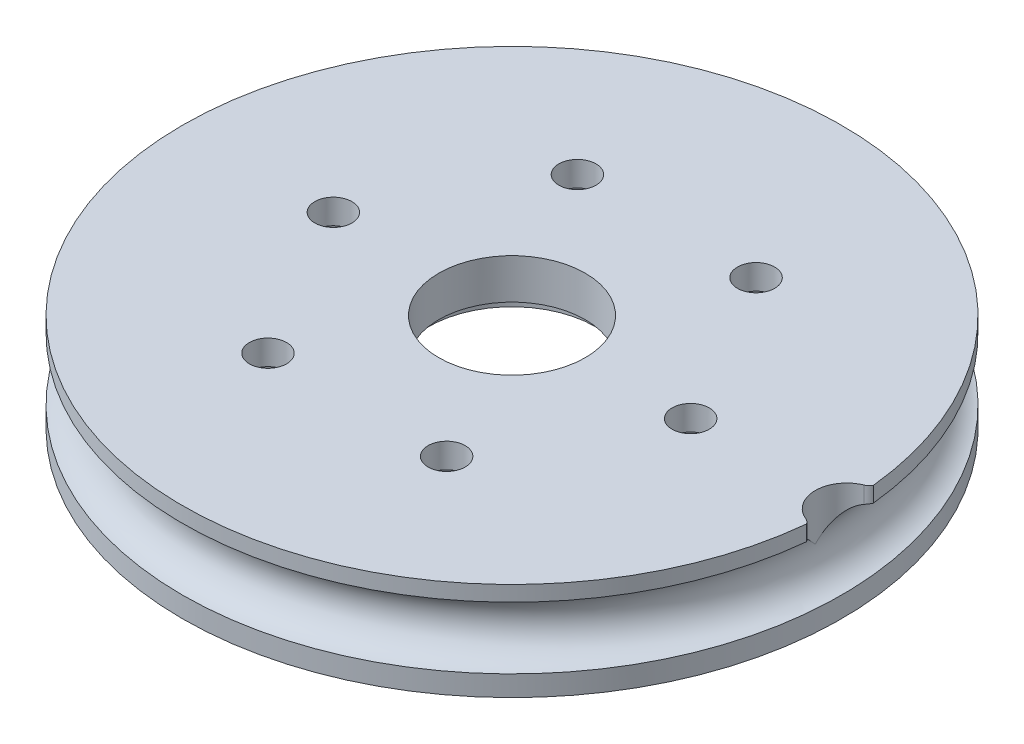
SolidWorks part; units mm, degrees
ref_plane "Front Plane" through (0, 0, 0) normal (0, 0, 1) x (1, 0, 0)
ref_plane "Top Plane" through (0, 0, 0) normal (0, 1, 0) x (1, 0, 0)
ref_plane "Right Plane" through (0, 0, 0) normal (1, 0, 0) x (0, 0, -1)
sketch "Sketch1" plane through (0, 0, 0) normal (0, 1, 0) x (1, 0, 0)
  line L0 (3.8128, 15.469) -> (8.2942, 33.6508) construction
  circle A0 centre (0, 0) radius 25.1 construction
  circle A1 centre (0, 25.1) radius 2
  circle A2 centre (11.6646, 22.2249) radius 2
  circle A3 centre (20.6569, 14.2584) radius 2
  circle A4 centre (24.917, 3.0255) radius 2
  circle A5 centre (23.4689, -8.9006) radius 2
  circle A6 centre (16.6444, -18.7876) radius 2
  circle A7 centre (6.0068, -24.3706) radius 2
  circle A8 centre (-6.0068, -24.3706) radius 2
  circle A9 centre (-16.6444, -18.7876) radius 2
  circle A10 centre (-23.4689, -8.9006) radius 2
  circle A11 centre (-24.917, 3.0255) radius 2
  circle A12 centre (-20.6569, 14.2584) radius 2
  arc A16 (1.6408, 23.5429) -> (9.4881, 21.6087) centre (5.6478, 22.9142) cw
  arc A17 (12.3938, 20.0837) -> (18.4433, 14.7242) centre (15.6497, 17.6649) cw
  arc A18 (20.3075, 12.0235) -> (23.1735, 4.4666) centre (22.0664, 8.3687) cw
  arc A19 (23.569, 1.2089) -> (22.5948, -6.8142) centre (23.4279, -2.8447) cw
  arc A20 (21.4311, -9.8826) -> (16.84, -16.534) centre (19.4224, -13.4063) cw
  arc A21 (14.3837, -18.7102) -> (7.2273, -22.4661) centre (10.9675, -20.8968) cw
  arc A22 (4.0411, -23.2514) -> (-4.0411, -23.2514) centre (0, -23.6) cw
  arc A23 (-7.2273, -22.4661) -> (-14.3837, -18.7102) centre (-10.9675, -20.8968) cw
  arc A24 (-16.84, -16.534) -> (-21.4311, -9.8826) centre (-19.4224, -13.4063) cw
  arc A25 (-22.5948, -6.8142) -> (-23.569, 1.2089) centre (-23.4279, -2.8447) cw
  arc A26 (-23.1735, 4.4666) -> (-20.3075, 12.0235) centre (-22.0664, 8.3687) cw
  arc A27 (-18.4433, 14.7242) -> (-12.3938, 20.0837) centre (-15.6497, 17.6649) cw
  circle A30 centre (0, 0) radius 4 construction
  circle A31 centre (0, 0) radius 23.6 construction
  circle A32 centre (0, 0) radius 32.15
  circle A33 centre (0, 0) radius 1.5
  circle A34 centre (-11.6646, 22.2249) radius 2
  arc A37 (-9.4881, 21.6087) -> (-1.6408, 23.5429) centre (-5.6478, 22.9142) cw
  dimension "D1" = 50.2
  dimension "D2" = 4
  dimension "D8" = 8
  dimension "D4" = 64.3
  dimension "D6" = 3
  dimension "D5" = 0
  dimension "D9" = 1.5
  dimension "D3" = 13
  dimension "D7" = 13
extrude "Boss-Extrude1" add sketch "Sketch1" along normal blind 4.5
sketch "Sketch2" plane through (0, 4.5, 0) normal (0, 1, 0) x (1, 0, 0)
  circle A0 centre (0, 0) radius 4 construction
  circle A2 centre (0, 0) radius 4
  circle A3 centre (0, 0) radius 32.15 construction
  circle A4 centre (0, 0) radius 1.5 construction
  circle A6 centre (0, 0) radius 32.15
extrude "Boss-Extrude2" add sketch "Sketch2" along normal blind 5
sketch "Sketch3" plane through (0, 9.5, 0) normal (0, 1, 0) x (1, 0, 0)
  line L1 (8.6603, 15) -> (-8.6603, 15) construction
  line L2 (-8.6603, 15) -> (-17.3205, 0) construction
  line L3 (-17.3205, 0) -> (-8.6603, -15) construction
  line L4 (-8.6603, -15) -> (8.6603, -15) construction
  line L5 (8.6603, -15) -> (17.3205, 0) construction
  line L6 (17.3205, 0) -> (8.6603, 15) construction
  circle A0 centre (0, 0) radius 15 construction
  circle A1 centre (-8.6603, 15) radius 1.8
  circle A2 centre (8.6603, 15) radius 1.8
  circle A3 centre (17.3205, 0) radius 1.8
  circle A4 centre (8.6603, -15) radius 1.8
  circle A5 centre (-8.6603, -15) radius 1.8
  circle A6 centre (-17.3205, 0) radius 1.8
  dimension "D1" = 3.6
  dimension "D2" = 30
extrude "Cut-Extrude1" cut sketch "Sketch3" against normal through all
sketch "Sketch5" plane through (0, 0, 0) normal (0, 0, 1) x (1, 0, 0)
  line L0 (-3, 11.5) -> (-3, 4.5)
  line L1 (-3, 4.5) -> (-8.1, 4.5)
  line L2 (-8.1, 4.5) -> (-8.1, 5.6)
  line L3 (-8.1, 5.6) -> (-7.1, 5.6)
  line L4 (-7.1, 5.6) -> (-7.1, 11.5)
  line L5 (-7.1, 11.5) -> (-3, 11.5)
  line L6 (0, 0) -> (0, 27.5187) construction
  line L7 (-19.1205, 4.5) -> (-15.5205, 4.5) construction
  line L10 (1.5, 0) -> (-1.5, 0) construction
  dimension "D1" = 1
  dimension "D2" = 6
  dimension "D3" = 14.2
  dimension "D4" = 1.1
  dimension "D5" = 7
revolve "Cut-Revolve1" cut sketch "Sketch5" angle 360 about L6
chamfer "Chamfer3" [suppressed] distance 0.5 angle 45
sketch "Sketch6" plane through (0, 0, 0) normal (0, -1, 0) x (1, 0, 0)
  circle A0 centre (0, 0) radius 25.1
  circle A1 centre (-6.0068, 24.3706) radius 1
  circle A2 centre (6.7008, 27.1864) radius 1
  circle A3 centre (19.2614, 23.774) radius 1
  circle A4 centre (28.7975, 14.9153) radius 1
  circle A5 centre (33.1245, 2.6397) radius 1
  circle A6 centre (31.251, -10.2406) radius 1
  circle A7 centre (23.6064, -20.7749) radius 1
  circle A8 centre (11.9418, -26.55) radius 1
  circle A9 centre (-1.0704, -26.2428) radius 1
  circle A10 centre (-12.4494, -19.9236) radius 1
  circle A11 centre (-19.5884, -9.0402) radius 1
  circle A12 centre (-20.8518, 3.9142) radius 1
  circle A13 centre (-15.9504, 15.9719) radius 1
  dimension "D2" = 2
  dimension "D1" = 13
sketch "Sketch7" plane through (0, 0, 0) normal (0, 0, 1) x (1, 0, 0)
  line L1 (0, 0) -> (0, 20.9814) construction
  circle A0 centre (32.45, 5) radius 3.05
  dimension "D1" = 6.1
  dimension "D2" = 64.9
  dimension "D3" = 5
revolve "Cut-Revolve2" cut sketch "Sketch7" angle 360 about L1
sketch "Sketch8" plane through (0, 9.5, 0) normal (0, 1, 0) x (1, 0, 0)
  circle A0 centre (32.45, 0) radius 3.05
  dimension "D1" = 6.1
extrude "Cut-Extrude2" cut sketch "Sketch8" against normal up to surface (1.4534 mm away) contours A0
fillet "Fillet1" radius 1 2 edges at (32.0081, 8.7676, -3.0178) (32.0081, 8.7676, 3.0178)
fillet "Fillet2" radius 0.5 26 edges at (5.5282, 0, 22.4288) (12.8524, 0, 24.4882) (15.3181, 0, 17.2906) (22.7605, 0, 15.7104) (21.5989, 0, 8.1914) (27.4544, 0, 3.3336) (22.9316, 0, -2.7844) (25.8589, 0, -9.807) (19.0109, 0, -13.1223) (18.3394, 0, -20.7009) (10.7351, 0, -20.454) (6.6185, 0, -26.8524) (0, 0, -23.1) (-6.6185, 0, -26.8524) (-10.7351, 0, -20.454) (-18.3394, 0, -20.7009) (-19.0109, 0, -13.1223) (-25.8589, 0, -9.807) (-22.9316, 0, -2.7844) (-27.4544, 0, 3.3336) (-21.5989, 0, 8.1914) (-22.7605, 0, 15.7104) (-15.3181, 0, 17.2906) (-12.8524, 0, 24.4882) (-5.5282, 0, 22.4288) (0, 0, 27.6561)
sketch "Sketch9" plane through (0, 4.5, 0) normal (0, -1, 0) x (1, 0, 0)
  line L0 (11.8934, -15) -> (10.2768, -12.2)
  line L1 (20.5537, 0) -> (18.9371, 2.8)
  line L2 (18.9371, 2.8) -> (15.7039, 2.8)
  line L3 (15.7039, 2.8) -> (14.0873, 0)
  line L4 (14.0873, 0) -> (15.7039, -2.8)
  line L5 (15.7039, -2.8) -> (18.9371, -2.8)
  line L6 (18.9371, -2.8) -> (20.5537, 0)
  line L7 (10.2768, -12.2) -> (7.0437, -12.2)
  line L8 (7.0437, -12.2) -> (5.4271, -15)
  line L9 (5.4271, -15) -> (7.0437, -17.8)
  line L10 (7.0437, -17.8) -> (10.2768, -17.8)
  line L11 (10.2768, -17.8) -> (11.8934, -15)
  line L12 (-7.0437, -17.8) -> (-5.4271, -15)
  line L13 (-5.4271, -15) -> (-7.0437, -12.2)
  line L14 (-7.0437, -12.2) -> (-10.2768, -12.2)
  line L15 (-10.2768, -12.2) -> (-11.8934, -15)
  line L16 (-11.8934, -15) -> (-10.2768, -17.8)
  line L17 (-10.2768, -17.8) -> (-7.0437, -17.8)
  line L18 (-18.9371, -2.8) -> (-15.7039, -2.8)
  line L19 (-15.7039, -2.8) -> (-14.0873, 0)
  line L20 (-14.0873, 0) -> (-15.7039, 2.8)
  line L21 (-15.7039, 2.8) -> (-18.9371, 2.8)
  line L22 (-18.9371, 2.8) -> (-20.5537, 0)
  line L23 (-20.5537, 0) -> (-18.9371, -2.8)
  line L24 (-11.8934, 15) -> (-10.2768, 12.2)
  line L25 (-10.2768, 12.2) -> (-7.0437, 12.2)
  line L26 (-7.0437, 12.2) -> (-5.4271, 15)
  line L27 (-5.4271, 15) -> (-7.0437, 17.8)
  line L28 (-7.0437, 17.8) -> (-10.2768, 17.8)
  line L29 (-10.2768, 17.8) -> (-11.8934, 15)
  line L30 (7.0437, 17.8) -> (5.4271, 15)
  line L31 (5.4271, 15) -> (7.0437, 12.2)
  line L32 (7.0437, 12.2) -> (10.2768, 12.2)
  line L33 (10.2768, 12.2) -> (11.8934, 15)
  line L34 (11.8934, 15) -> (10.2768, 17.8)
  line L35 (10.2768, 17.8) -> (7.0437, 17.8)
  circle A0 centre (17.3205, 0) radius 2.8 construction
  circle A1 centre (8.6603, -15) radius 2.8 construction
  circle A2 centre (-8.6603, -15) radius 2.8 construction
  circle A3 centre (-17.3205, 0) radius 2.8 construction
  circle A4 centre (-8.6603, 15) radius 2.8 construction
  circle A5 centre (8.6603, 15) radius 2.8 construction
  dimension "D2" = 5.6
  dimension "D1" = 6
extrude "Cut-Extrude3" cut sketch "Sketch9" against normal blind 2.6
sketch "Sketch11" plane through (0, 9.5, 0) normal (0, 1, 0) x (1, 0, 0)
  circle A2 centre (0, 0) radius 31.95
  circle A3 centre (0, 0) radius 31.95
  dimension "D1" = 0.2
extrude "Cut-Extrude5" cut sketch "Sketch11" against normal through all flip side to cut
equation "\"N\"= 13"
equation "\"Rr\"= 2"
equation "\"R\"= 25.1"
equation "\"E\"= 1.5"
equation "\"D3@Sketch1\"=\"N\""
equation "\"D7@Sketch1\"=\"N\""
equation "\"D2@Sketch1\"=\"Rr\" * 2"
equation "\"D1@Sketch1\"=\"R\" * 2"
